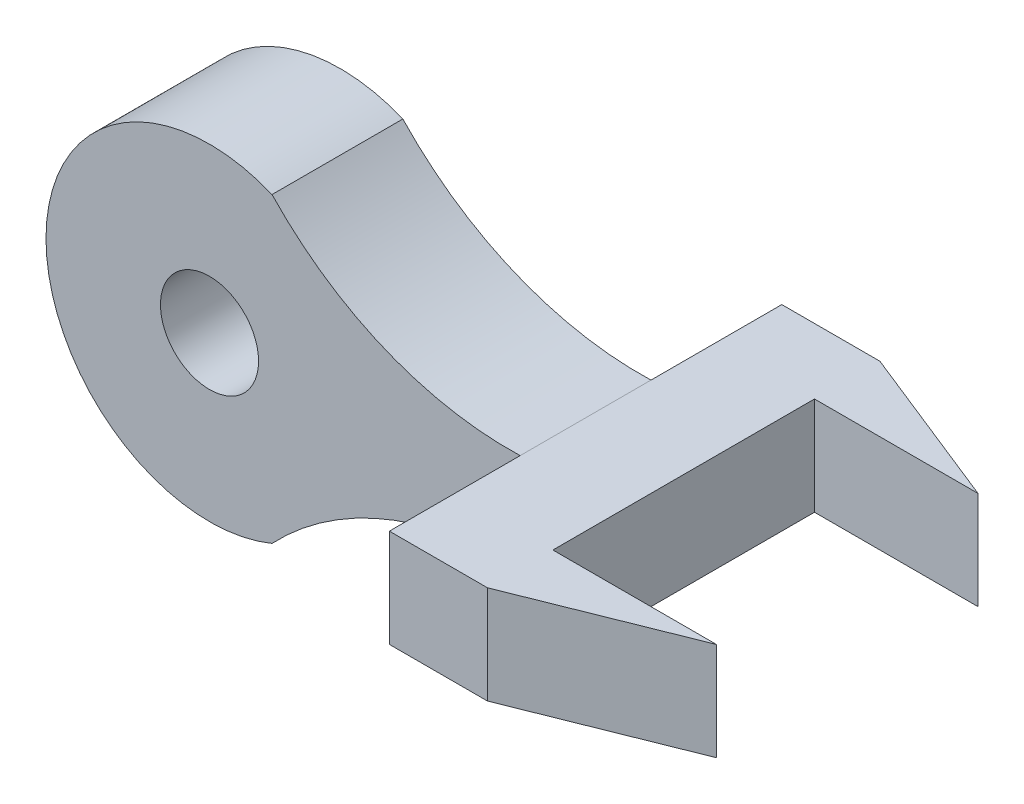
SolidWorks part; units mm, degrees
ref_plane "Front Plane" through (0, 0, 0) normal (0, 0, 1) x (1, 0, 0)
ref_plane "Top Plane" through (0, 0, 0) normal (0, 1, 0) x (1, 0, 0)
ref_plane "Right Plane" through (0, 0, 0) normal (1, 0, 0) x (0, 0, -1)
sketch "Sketch1" plane through (0, 0, 0) normal (0, 0, 1) x (1, 0, 0)
  line L2 (95, 15) -> (0, 15) construction
  line L3 (0, 15) -> (0, -15) construction
  line L4 (95, 15) -> (125, 15)
  line L6 (94.5209, -15) -> (125, -15)
  line L7 (125, 15) -> (125, -15)
  line L8 (0, -15) -> (94.5209, -15) construction
  circle A0 centre (0, 0) radius 15
  arc A1 (19.1173, 46.201) -> (19.1173, -46.201) centre (0, 0) ccw
  arc A2 (19.1173, 46.201) -> (95, 15) centre (91.7397, 114.9468) ccw
  arc A3 (19.1173, -46.201) -> (94.5209, -15) centre (91.7263, -114.9609) cw
  point P13 (125, 0)
  dimension "D1" = 100
  dimension "D2" = 30
  dimension "D3" = 125
  dimension "D4" = 30
extrude "Boss-Extrude1" add sketch "Sketch1" along normal mid plane 40
sketch "Sketch5" plane through (0, 0, 0) normal (0, 0, 1) x (1, 0, 0)
  line L1 (125, -15) -> (95, -15)
  line L2 (125, -15) -> (125, 15)
  line L3 (125, 15) -> (95, 15)
  line L4 (95, -15) -> (95, 15)
extrude "Boss-Extrude2" add sketch "Sketch5" along normal mid plane 120
sketch "Sketch6" plane through (0, 15, 0) normal (0, 1, 0) x (1, 0, 0)
  line L0 (95, 20) -> (125, 60) construction
  line L1 (125, 60) -> (125, -60) construction
  line L2 (125, -60) -> (95, -20) construction
  line L3 (125, 60) -> (175, 40)
  line L4 (175, 40) -> (125, 40)
  line L5 (125, 40) -> (125, 60)
  line L6 (125, -60) -> (175, -40)
  line L7 (175, -40) -> (125, -40)
  line L8 (125, -40) -> (125, -60)
  dimension "D1" = 50
  dimension "D2" = 50
extrude "Boss-Extrude3" add sketch "Sketch6" against normal up to surface (30 mm away) up to face at (102.3802, -15, 0)
sketch "Sketch7" plane through (0, 0, 0) normal (0, 1, 0) x (1, 0, 0)
  line L0 (125, 40) -> (175, -40) construction
  point P4 (150, 0)
sketch "Sketch8" plane through (0, 0, 0) normal (0, 0, 1) x (1, 0, 0)
  line L0 (175, -15) -> (175, 15) construction
  point P0 (175, 0)
  point P1 (-206.6506, 45.7468)
